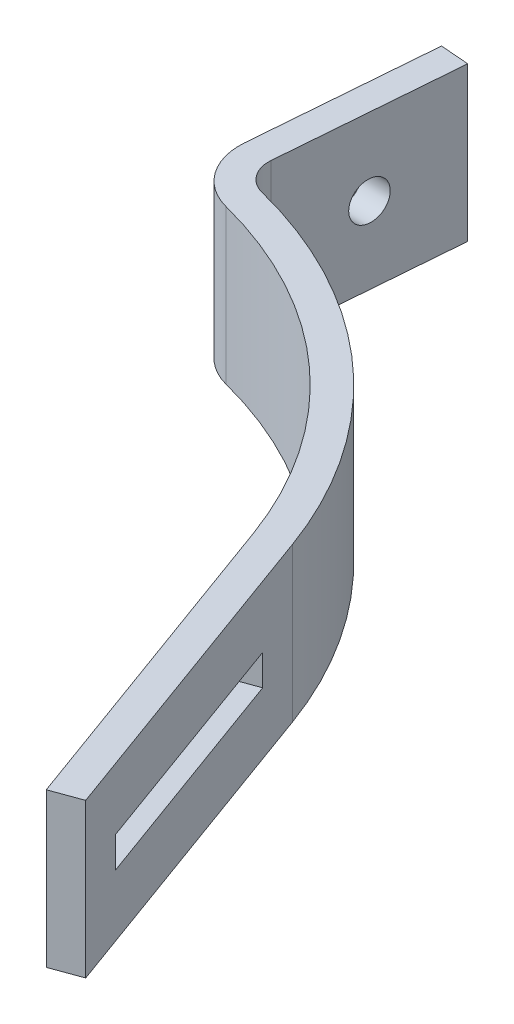
SolidWorks part; units mm, degrees
ref_plane "Спереди" through (0, 0, 0) normal (0, 0, 1) x (1, 0, 0)
ref_plane "Сверху" through (0, 0, 0) normal (0, 1, 0) x (1, 0, 0)
ref_plane "Справа" through (0, 0, 0) normal (1, 0, 0) x (0, 0, -1)
sketch "Эскиз1" plane through (0, 0, 0) normal (0, 1, 0) x (1, 0, 0)
  line L0 (-28.1183, 42.7403) -> (-27.1709, 54.5665)
  line L1 (-29.9725, 42.8642) -> (-29.0231, 54.7149)
  line L2 (-7.6955, 21.1431) -> (0, 0)
  line L3 (-27.1709, 54.5665) -> (-29.0231, 54.7149)
  line L4 (0, 0) -> (1.8794, 0.684)
  line L5 (-5.8161, 21.8271) -> (1.8794, 0.684)
  arc A0 (-7.6955, 21.1431) -> (-26.9879, 38.6725) centre (-34.0068, 11.5665) ccw
  arc A1 (-5.8161, 21.8271) -> (-26.6173, 40.6422) centre (-34.0068, 11.5665) ccw
  arc A2 (-28.1183, 42.7403) -> (-26.6173, 40.6422) centre (-26.1246, 42.5806) ccw
  arc A3 (-29.9725, 42.8642) -> (-26.9879, 38.6725) centre (-25.9852, 42.5448) ccw
  dimension "D1" = 2
extrude "Бобышка-Вытянуть1" add sketch "Эскиз1" along normal blind 10
sketch "Эскиз2" plane through (0, 0, 0) normal (1, 0, 0) x (0, 0, -1)
  circle A0 centre (48.6534, 5) radius 1.25
  dimension "D1" = 2.5
extrude "Вырез-Вытянуть1" cut sketch "Эскиз2" against normal through all
sketch "Эскиз3" plane through (1.8794, 0, -0.684) normal (0.9397, 0, -0.342) x (-0.342, 0, -0.9397)
  line L3 (3.25, 4) -> (19.25, 4)
  line L4 (3.25, 6) -> (19.25, 6)
  line L8 (3.25, 6) -> (3.25, 4)
  line L9 (19.25, 4) -> (19.25, 6)
extrude "Вырез-Вытянуть2" cut sketch "Эскиз3" against normal blind 10
sketch "Эскиз4" plane through (0, 10, 0) normal (0, 1, 0) x (1, 0, 0)
  line L1 (-33.7225, 57.2733) -> (-33.7225, 30.5431)
